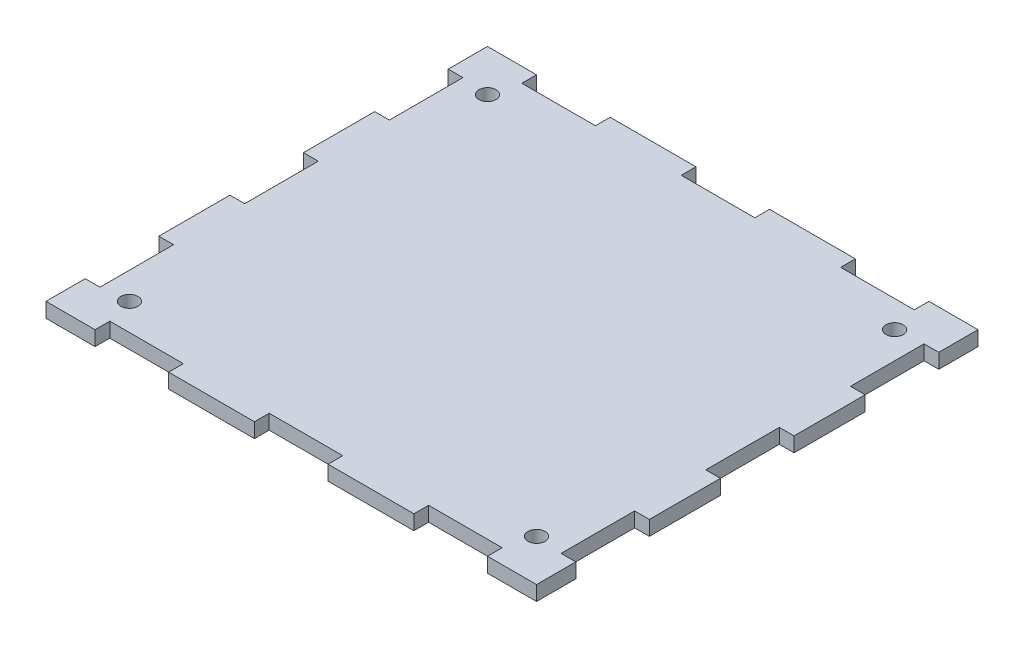
SolidWorks part; units mm, degrees
ref_plane "前视基准面" through (0, 0, 0) normal (0, 0, 1) x (1, 0, 0)
ref_plane "上视基准面" through (0, 0, 0) normal (0, 1, 0) x (1, 0, 0)
ref_plane "右视基准面" through (0, 0, 0) normal (1, 0, 0) x (0, 0, -1)
sketch "草图1" plane through (0, 0, 0) normal (0, 1, 0) x (1, 0, 0)
  line L0 (-50, 0) -> (50, 0) construction
  line L1 (-50, -45) -> (-40, -45)
  line L2 (-50, -45) -> (-50, -37)
  line L3 (-50, 45) -> (-40, 45)
  line L4 (50, -45) -> (50, -37)
  line L5 (-50, -45) -> (50, 45) construction
  line L6 (-50, 45) -> (50, -45) construction
  line L7 (25, -45) -> (25, -42)
  line L8 (-40, -45) -> (-40, -42)
  line L9 (-40, -42) -> (-25, -42)
  line L10 (-25, -45) -> (-25, -42)
  line L11 (7.5, -45) -> (25, -45)
  line L12 (-7.5, -45) -> (-7.5, -42)
  line L13 (-7.5, -42) -> (7.5, -42)
  line L14 (7.5, -45) -> (7.5, -42)
  line L15 (0, -45) -> (0, 45) construction
  line L16 (-25, -45) -> (-7.5, -45)
  line L17 (40, -45) -> (40, -42)
  line L18 (40, -42) -> (25, -42)
  line L19 (40, -45) -> (50, -45)
  line L20 (25, 45) -> (25, 42)
  line L21 (40, 45) -> (40, 42)
  line L22 (40, 42) -> (25, 42)
  line L23 (7.5, 45) -> (7.5, 42)
  line L24 (-7.5, 42) -> (7.5, 42)
  line L25 (-7.5, 45) -> (-7.5, 42)
  line L26 (-25, 45) -> (-25, 42)
  line L27 (-40, 42) -> (-25, 42)
  line L28 (-40, 45) -> (-40, 42)
  line L29 (-25, 45) -> (-7.5, 45)
  line L30 (7.5, 45) -> (25, 45)
  line L31 (40, 45) -> (50, 45)
  line L32 (-50, 7.5) -> (-50, 22)
  line L33 (-50, -37) -> (-47, -37)
  line L34 (-50, 37) -> (-47, 37)
  line L35 (-50, -22) -> (-47, -22)
  line L36 (-47, -37) -> (-47, -22)
  line L37 (-50, 7.5) -> (-47, 7.5)
  line L38 (-50, -22) -> (-50, -7.5)
  line L39 (-50, -7.5) -> (-47, -7.5)
  line L40 (-47, 7.5) -> (-47, -7.5)
  line L41 (-50, 22) -> (-47, 22)
  line L42 (-47, 37) -> (-47, 22)
  line L43 (-50, 37) -> (-50, 45)
  line L44 (50, -37) -> (47, -37)
  line L45 (47, -37) -> (47, -22)
  line L46 (50, -22) -> (47, -22)
  line L47 (50, -7.5) -> (47, -7.5)
  line L48 (47, 7.5) -> (47, -7.5)
  line L49 (50, 7.5) -> (47, 7.5)
  line L50 (50, 22) -> (47, 22)
  line L51 (47, 37) -> (47, 22)
  line L52 (50, 37) -> (47, 37)
  line L53 (50, 37) -> (50, 45)
  line L54 (50, 7.5) -> (50, 22)
  line L55 (50, -22) -> (50, -7.5)
  line L57 (-41.5, -36.5) -> (41.5, -36.5) construction
  line L58 (-41.5, -36.5) -> (-41.5, 36.5) construction
  line L59 (-41.5, 36.5) -> (41.5, 36.5) construction
  line L60 (41.5, -36.5) -> (41.5, 36.5) construction
  line L61 (-41.5, -36.5) -> (41.5, 36.5) construction
  line L62 (-41.5, 36.5) -> (41.5, -36.5) construction
  circle A0 centre (-41.5, 36.5) radius 1.75
  circle A1 centre (41.5, 36.5) radius 1.75
  circle A2 centre (41.5, -36.5) radius 1.75
  circle A3 centre (-41.5, -36.5) radius 1.75
  point P0 (0, 0)
  point P14 (0, -42)
  point P17 (0, 0)
  point P20 (0, 0)
  point P45 (-47, 0)
  point P62 (0, 0)
  dimension "D15" = 3.5
  dimension "D1" = 90
  dimension "D2" = 100
  dimension "D3" = 3
  dimension "D4" = 3
  dimension "D5" = 10
  dimension "D6" = 15
  dimension "D7" = 15
  dimension "D8" = 8
  dimension "D9" = 3
  dimension "D10" = 15
  dimension "D11" = 3
  dimension "D12" = 15
  dimension "D13" = 83
  dimension "D14" = 73
extrude "凸台-拉伸1" add sketch "草图1" along normal blind 3
